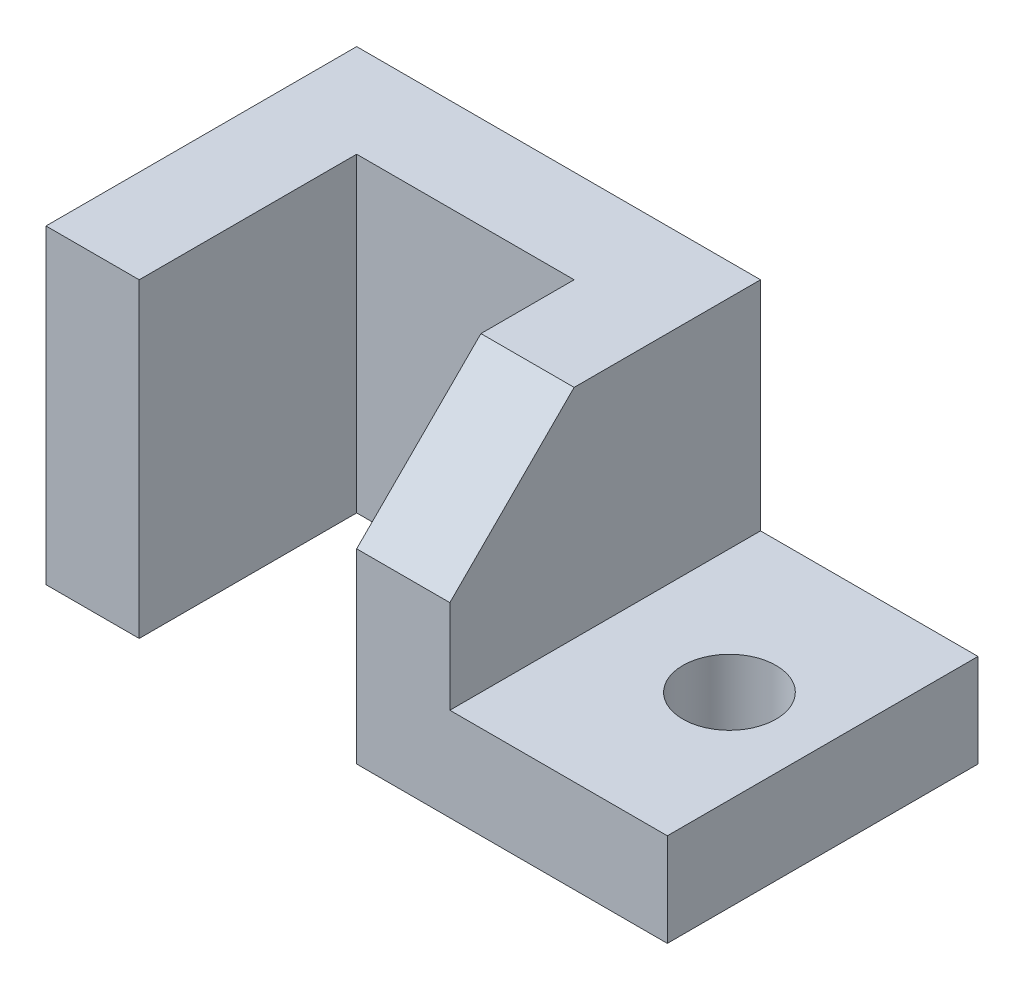
SolidWorks part; units mm, degrees
ref_plane "Front Plane" through (0, 0, 0) normal (0, 0, 1) x (1, 0, 0)
ref_plane "Top Plane" through (0, 0, 0) normal (0, 1, 0) x (1, 0, 0)
ref_plane "Right Plane" through (0, 0, 0) normal (1, 0, 0) x (0, 0, -1)
sketch "Sketch1" plane through (0, 0, 0) normal (0, 0, 1) x (1, 0, 0)
  line L0 (0, 63.5) -> (19.05, 63.5)
  line L1 (19.05, 63.5) -> (19.05, 19.05)
  line L2 (19.05, 19.05) -> (63.5, 19.05)
  line L3 (63.5, 19.05) -> (63.5, 0)
  line L4 (63.5, 0) -> (0, 0)
  line L5 (0, 0) -> (0, 63.5)
  point P2 (-74.8109, 26.8883)
  point P7 (-77.5891, 26.8883)
  point P8 (-46.8312, 26.8883)
  point P9 (-77.5891, 59.6305)
  point P10 (0, 0)
  point P11 (-97.0359, 7.8383)
  point P12 (0, 0)
  point P14 (0, 0)
  point P15 (0, 0)
  point P16 (0, 0)
  point P17 (0, 0)
  point P18 (0, 0)
  point P19 (0, 0)
  point P20 (19.05, 19.05)
  dimension "D1" = 19.05
  dimension "D2" = 63.5
  dimension "D3" = 19.05
  dimension "D4" = 63.5
extrude "Boss-Extrude1" add sketch "Sketch1" along normal blind 63.5
sketch "Sketch2" plane through (0, 63.5, 0) normal (0, 1, 0) x (1, 0, 0)
  line L0 (0, 0) -> (-63.5, 0)
  line L1 (-63.5, 0) -> (-63.5, -63.5)
  line L2 (-63.5, -63.5) -> (-44.45, -63.5)
  line L3 (-44.45, -63.5) -> (-44.45, -19.05)
  line L4 (-44.45, -19.05) -> (0, -19.05)
  line L5 (0, -19.05) -> (0, 0)
  line L6 (0, -63.5) -> (0, 0) construction
  point P9 (0, 0)
  dimension "D1" = 19.05
  dimension "D2" = 19.05
  dimension "D3" = 63.5
  dimension "D4" = 63.5
  dimension "D5" = 0
extrude "Boss-Extrude2" add sketch "Sketch2" against normal blind 63.5
sketch "Sketch3" plane through (0, 19.05, 0) normal (0, 1, 0) x (1, 0, 0)
  line L0 (63.5, 0) -> (19.05, 0) construction
  line L1 (63.5, -63.5) -> (63.5, 0) construction
  circle A0 centre (44.45, -31.75) radius 9.525
  dimension "D1" = 19.05
  dimension "D3" = 19.05
  dimension "D2" = 31.75
extrude "Cut-Extrude1" cut sketch "Sketch3" against normal through all contours A0
sketch "Sketch4" plane through (19.05, 0, 0) normal (1, 0, 0) x (0, 0, -1)
  line L17 (-63.5, 63.5) -> (-38.1, 63.5)
  line L18 (-63.5, 63.5) -> (0, 63.5) construction
  line L19 (-38.1, 63.5) -> (-63.5, 38.1)
  line L20 (-63.5, 19.05) -> (-63.5, 63.5) construction
  line L21 (-63.5, 38.1) -> (-63.5, 63.5)
  dimension "D1" = 25.4
  dimension "D2" = 45
extrude "Cut-Extrude2" cut sketch "Sketch4" against normal up to next
